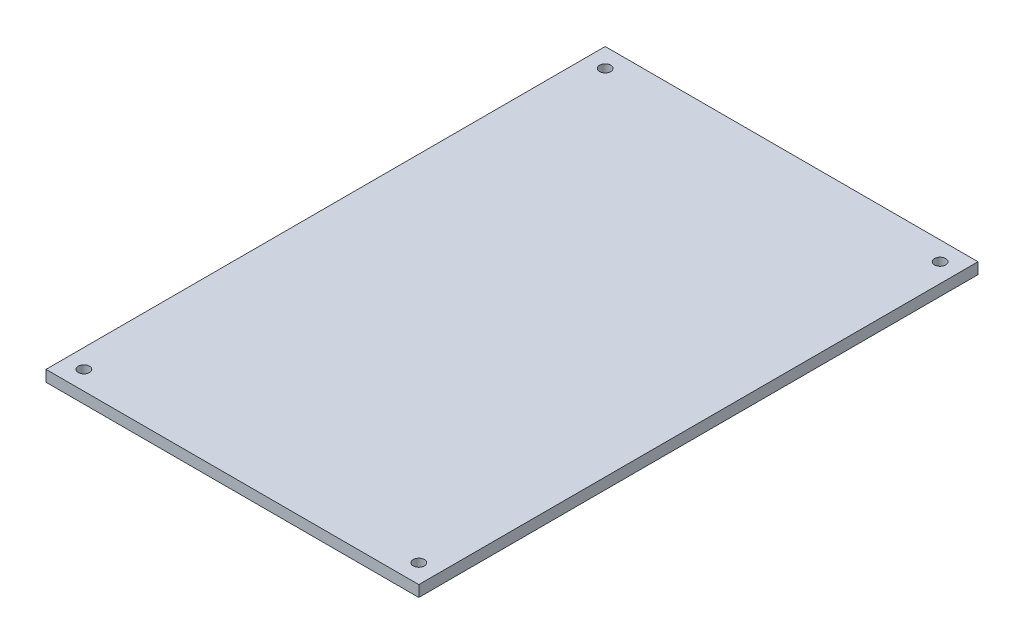
SolidWorks part; units mm, degrees
ref_plane "Front Plane" through (0, 0, 0) normal (0, 0, 1) x (1, 0, 0)
ref_plane "Top Plane" through (0, 0, 0) normal (0, 1, 0) x (1, 0, 0)
ref_plane "Right Plane" through (0, 0, 0) normal (1, 0, 0) x (0, 0, -1)
sketch "Sketch1" plane through (0, 0, 0) normal (0, 1, 0) x (1, 0, 0)
  line L1 (-50, -75) -> (50, -75)
  line L2 (-50, -75) -> (-50, 75)
  line L3 (-50, 75) -> (50, 75)
  line L4 (50, -75) -> (50, 75)
  line L5 (-50, -75) -> (50, 75) construction
  line L6 (-50, 75) -> (50, -75) construction
  point P0 (0, 0)
  dimension "D1" = 150
  dimension "D2" = 100
extrude "Boss-Extrude1" add sketch "Sketch1" along normal blind 3
sketch "Sketch2" plane through (0, 3, 0) normal (0, 1, 0) x (1, 0, 0)
  line L0 (0, 75) -> (0, -75) construction
  line L1 (50, 75) -> (-50, 75) construction
  line L2 (-50, -75) -> (50, -75) construction
  line L3 (-50, 75) -> (-50, -75) construction
  line L4 (50, -75) -> (50, 75) construction
  circle A2 centre (-44.92, 69.92) radius 1.5
  circle A3 centre (44.92, 69.92) radius 1.5
  circle A4 centre (-44.92, -69.92) radius 1.5
  circle A5 centre (44.92, -69.92) radius 1.5
  dimension "D7" = 5.08
  dimension "D8" = 5.08
  dimension "D9" = 5.08
  dimension "D10" = 5.08
  dimension "D11" = 5.08
  dimension "D12" = 5.08
  dimension "D13" = 5.08
  dimension "D14" = 5.08
  dimension "D23" = 3
  dimension "D24" = 3
  dimension "D25" = 3
  dimension "D26" = 3
extrude "Cut-Extrude1" cut sketch "Sketch2" against normal blind 3
